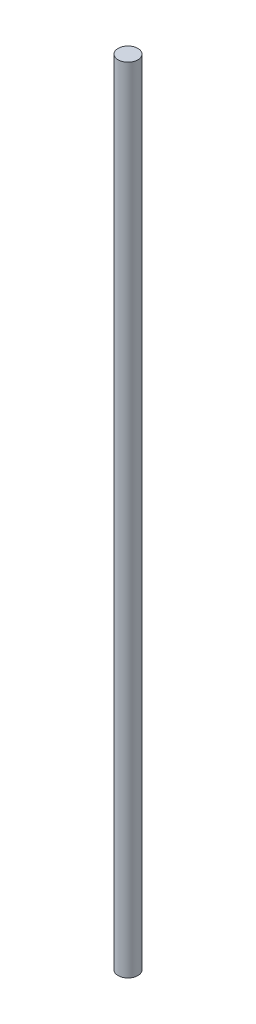
SolidWorks part; units mm, degrees
ref_plane "Front Plane" through (0, 0, 0) normal (0, 0, 1) x (1, 0, 0)
ref_plane "Top Plane" through (0, 0, 0) normal (0, 1, 0) x (1, 0, 0)
ref_plane "Right Plane" through (0, 0, 0) normal (1, 0, 0) x (0, 0, -1)
sketch "Sketch1" plane through (0, 0, 0) normal (0, 1, 0) x (1, 0, 0)
  circle A0 centre (0, 0) radius 2.75
  dimension "D1" = 5.5
extrude "Boss-Extrude1" add sketch "Sketch1" along normal mid plane 220
